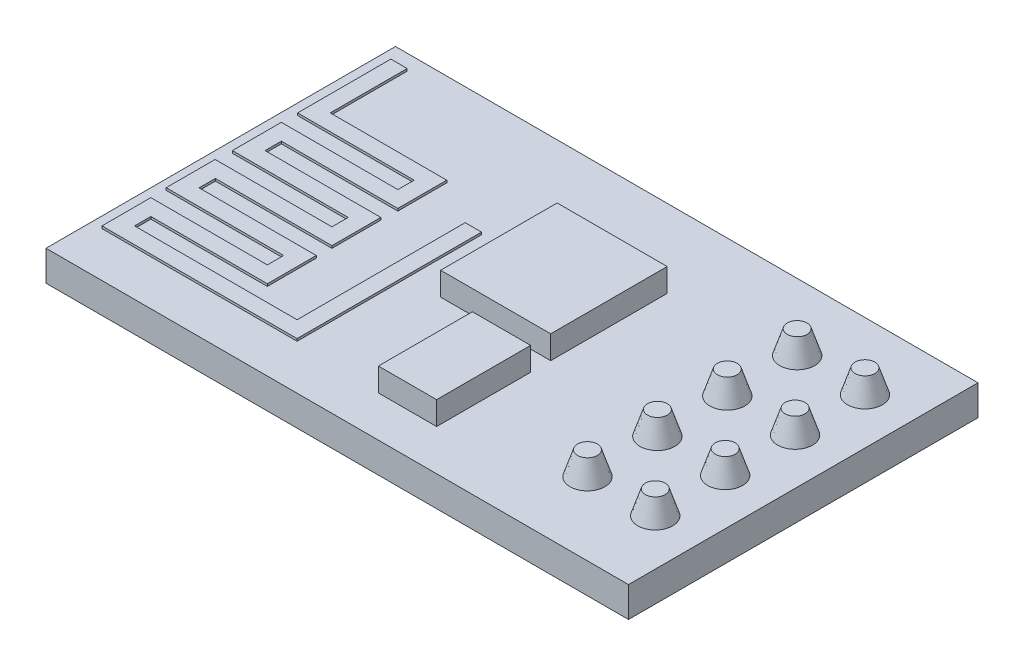
SolidWorks part; units mm, degrees
ref_plane "Front Plane" through (0, 0, 0) normal (0, 0, 1) x (1, 0, 0)
ref_plane "Top Plane" through (0, 0, 0) normal (0, 1, 0) x (1, 0, 0)
ref_plane "Right Plane" through (0, 0, 0) normal (1, 0, 0) x (0, 0, -1)
sketch "Sketch1" plane through (0, 0, 0) normal (0, 1, 0) x (1, 0, 0)
  line L1 (-12.5, 7.5) -> (12.5, 7.5)
  line L2 (-12.5, 7.5) -> (-12.5, -7.5)
  line L3 (-12.5, -7.5) -> (12.5, -7.5)
  line L4 (12.5, 7.5) -> (12.5, -7.5)
  line L5 (-12.5, 7.5) -> (12.5, -7.5) construction
  line L6 (-12.5, -7.5) -> (12.5, 7.5) construction
  point P0 (0, 0)
  dimension "D1" = 15
  dimension "D2" = 25
extrude "Boss-Extrude1" add sketch "Sketch1" along normal blind 1.3
sketch "Sketch2" plane through (0, 1.3, 0) normal (0, 1, 0) x (1, 0, 0)
  line L0 (-3.6547, -5.5693) -> (-12.0308, -5.5693)
  line L1 (-3.6547, -5.5693) -> (-3.6547, 2.3462)
  line L2 (-3.6547, 2.3462) -> (-4.3547, 2.3462)
  line L3 (-4.3547, 2.3462) -> (-4.3547, -4.8693)
  line L4 (-4.3547, -4.8693) -> (-11.3308, -4.8693)
  line L5 (-11.3308, -4.8693) -> (-11.3308, -4.1693)
  line L6 (-11.3308, -4.1693) -> (-6.3308, -4.1693)
  line L7 (-6.3308, -4.1693) -> (-6.3308, -2.0693)
  line L8 (-6.3308, -2.0693) -> (-11.3605, -2.0693)
  line L9 (-11.3605, -2.0693) -> (-11.3605, -1.3693)
  line L10 (-11.3605, -1.3693) -> (-6.3605, -1.3693)
  line L11 (-6.3605, -1.3693) -> (-6.3605, 0.7307)
  line L12 (-6.3605, 0.7307) -> (-11.3308, 0.7307)
  line L13 (-11.3308, 0.7307) -> (-11.3308, 1.4307)
  line L15 (-12.0308, -5.5693) -> (-12.0308, -3.4693)
  line L16 (-12.0308, -3.4693) -> (-7.0308, -3.4693)
  line L17 (-7.0308, -3.4693) -> (-7.0308, -2.7693)
  line L18 (-7.0308, -2.7693) -> (-12.0717, -2.7693)
  line L19 (-12.0717, -2.7693) -> (-12.0717, -0.6693)
  line L20 (-12.0717, -0.6693) -> (-7.0605, -0.6693)
  line L21 (-7.0605, -0.6693) -> (-7.0605, 0.0307)
  line L22 (-7.0605, 0.0307) -> (-12.0308, 0.0307)
  line L23 (-12.0308, 0.0307) -> (-12.0308, 2.1307)
  line L24 (-12.0308, 2.1307) -> (-7.0308, 2.1307)
  line L25 (-7.0308, 2.1307) -> (-7.0308, 2.8307)
  line L26 (-7.0308, 2.8307) -> (-12.0308, 2.8307)
  line L27 (-12.0308, 2.8307) -> (-12.0308, 6.8307)
  line L28 (-12.0308, 6.8307) -> (-11.3308, 6.8307)
  line L29 (-11.3308, 6.8307) -> (-11.3308, 3.5307)
  line L30 (-11.3308, 3.5307) -> (-6.3308, 3.5307)
  line L31 (-6.3308, 3.5307) -> (-6.3308, 1.4307)
  line L32 (-6.3308, 1.4307) -> (-11.3308, 1.4307)
  dimension "D1" = 0.7
  dimension "D2" = 0.7
  dimension "D3" = 0.7
  dimension "D4" = 0.7
  dimension "D5" = 0.7
  dimension "D6" = 0.7
  dimension "D7" = 0.7
  dimension "D8" = 0.7
  dimension "D9" = 0.7
  dimension "D10" = 0.7
  dimension "D11" = 0.7
  dimension "D12" = 0.7
  dimension "D13" = 0.7
  dimension "D14" = 5
  dimension "D15" = 5
  dimension "D16" = 5
  dimension "D17" = 0.7
  dimension "D18" = 5
  dimension "D19" = 4
  dimension "D20" = 0.7
extrude "Boss-Extrude2" add sketch "Sketch2" along normal blind 0.1
sketch "Sketch3" plane through (0, 1.3, 0) normal (0, 1, 0) x (1, 0, 0)
  line L1 (-2.2143, 4.1512) -> (2.5095, 4.1512)
  line L2 (-2.2143, 4.1512) -> (-2.2143, -0.8488)
  line L3 (-2.2143, -0.8488) -> (2.5095, -0.8488)
  line L4 (2.5095, 4.1512) -> (2.5095, -0.8488)
  line L5 (-2.2143, 4.1512) -> (2.5095, -0.8488) construction
  line L6 (-2.2143, -0.8488) -> (2.5095, 4.1512) construction
  line L7 (0.0095, -1.7099) -> (2.5095, -1.7099)
  line L8 (0.0095, -1.7099) -> (0.0095, -5.7448)
  line L9 (0.0095, -5.7448) -> (2.5095, -5.7448)
  line L10 (2.5095, -1.7099) -> (2.5095, -5.7448)
  line L11 (0.0095, -1.7099) -> (2.5095, -5.7448) construction
  line L12 (0.0095, -5.7448) -> (2.5095, -1.7099) construction
  point P0 (0.1476, 1.6512)
  point P5 (1.2595, -3.7273)
  dimension "D1" = 5
  dimension "D2" = 2.5
extrude "Boss-Extrude3" add sketch "Sketch3" along normal blind 1
sketch "Sketch4" plane through (0, 1.3, 0) normal (0, 1, 0) x (1, 0, 0)
  circle A0 centre (7.6087, 4.6312) radius 0.75
  circle A1 centre (10.5176, 4.6312) radius 0.75
  circle A2 centre (7.6087, 1.6312) radius 0.75
  circle A3 centre (10.5176, 1.6312) radius 0.75
  circle A4 centre (7.6087, -1.3688) radius 0.75
  circle A5 centre (10.5176, -1.3688) radius 0.75
  circle A6 centre (7.6087, -4.3688) radius 0.75
  circle A7 centre (10.5176, -4.3688) radius 0.75
  dimension "D1" = 1.5
  dimension "D2" = 1.5
  dimension "D3" = 4
extrude "Boss-Extrude4" add sketch "Sketch4" along normal blind 1 draft 18 contours A0 | A3 | A1 | A2 | A4 | A6 | A7 | A5
